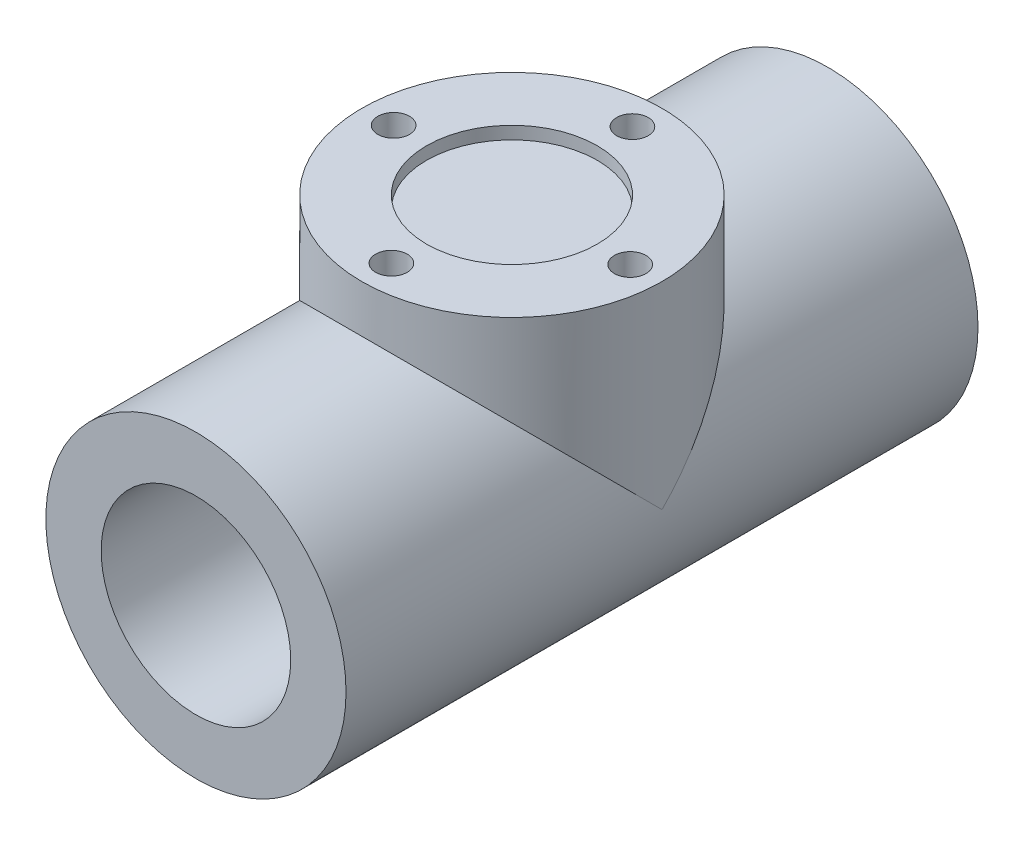
SolidWorks part; units mm, degrees
ref_plane "Front Plane" through (0, 0, 0) normal (0, 0, 1) x (1, 0, 0)
ref_plane "Top Plane" through (0, 0, 0) normal (0, 1, 0) x (1, 0, 0)
ref_plane "Right Plane" through (0, 0, 0) normal (1, 0, 0) x (0, 0, -1)
sketch "Sketch1" plane through (0, 0, 0) normal (0, 0, 1) x (1, 0, 0)
  circle A0 centre (0, 0) radius 47.5
  circle A1 centre (0, 0) radius 30
  dimension "D1" = 95
  dimension "D2" = 60
extrude "Boss-Extrude1" add sketch "Sketch1" along normal blind 200
ref_plane "Plane1" through (0, 62.5, 0) normal (0, 1, 0) x (1, 0, 0)
sketch "Sketch2" plane through (0, 62.5, 0) normal (0, 1, 0) x (1, 0, 0)
  line L0 (0, 0) -> (0, -200) construction
  line L1 (-47.5, -200) -> (47.5, -200) construction
  line L2 (47.5, -100) -> (-47.5, -100) construction
  line L3 (47.5, -200) -> (47.5, 0) construction
  line L4 (-47.5, 0) -> (-47.5, -200) construction
  circle A0 centre (0, -100) radius 47.5
extrude "Boss-Extrude2" add sketch "Sketch2" against normal blind 62.5
sketch "Sketch3" plane through (0, 62.5, 0) normal (0, 1, 0) x (1, 0, 0)
  circle A0 centre (0, -100) radius 27
  dimension "D1" = 54
extrude "Cut-Extrude1" cut sketch "Sketch3" against normal blind 4
hole_wizard "Ø1.0mm Dowel Hole1" positions "3DSketch2" profile "Sketch6" hole size "Ø1.0" standard "ISO"
sketch3d "3DSketch2"
  line L0 (0, 58.5, 100) -> (0, 62.5, 100) construction
  circle A0 centre (0, 58.5, 100) radius 38
  point P0 (0.3507, 62.5, 62.2127)
  point P2 (0.3507, 62.5, 62.2127)
  point P4 (0.3507, 62.5, 62.2127)
  point P6 (0.3507, 62.5, 62.2127)
  point P11 (-0.0371, 96.2889, 103.9998)
  point P15 (0, 0, 0)
  point P16 (0, 0, 0)
  point P17 (0, 0, 0)
  point P18 (0, 0, 0)
  dimension "D1" = 76
sketch "Sketch6" plane through (0.3507, 62.5, 62.2127) normal (1, 0, 0) x (0, 0, 1)
  line L0 (0, 0) -> (0, 23.0043)
  line L1 (0, 23.0043) -> (5, 20)
  line L2 (5, 20) -> (5, 0)
  line L5 (5, 0) -> (0, 0)
  line L10 (0, 23.0043) -> (-5, 20) construction
  line L11 (0, -6.35) -> (0, 107.95) construction
  dimension "Hole Dia." = 10
  dimension "Hole Depth" = 20
  dimension "Drill Angle" = 118
pattern_circular "CirPattern1" count 4 over 360 about axis through (0, 0, 100) along (0, 1, 0) of "Ø1.0mm Dowel Hole1"
